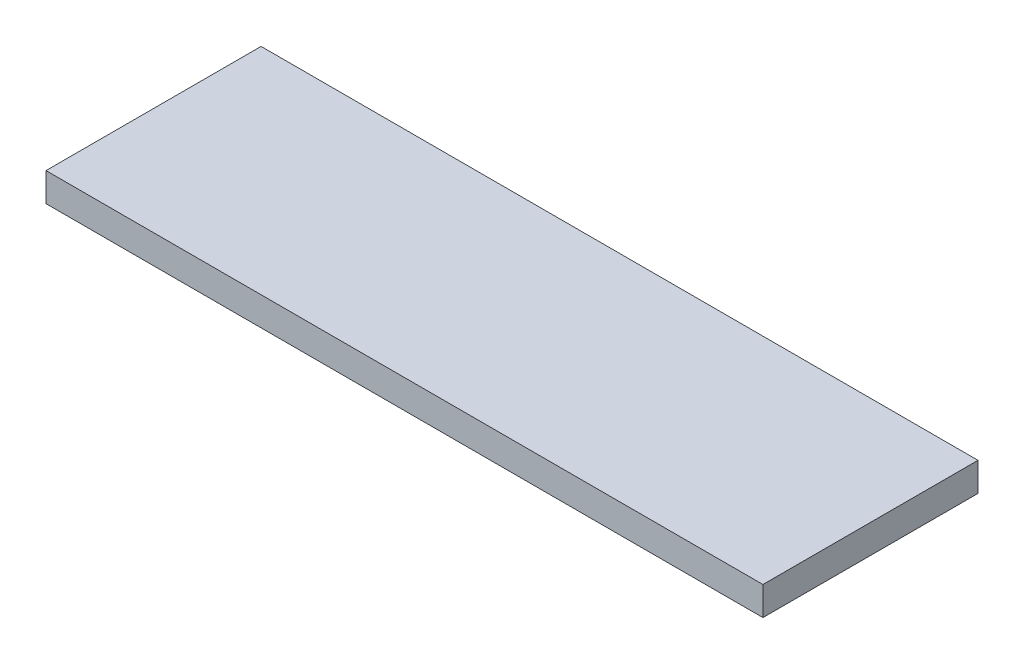
SolidWorks part; units mm, degrees
ref_plane "Front Plane" through (0, 0, 0) normal (0, 0, 1) x (1, 0, 0)
ref_plane "Top Plane" through (0, 0, 0) normal (0, 1, 0) x (1, 0, 0)
ref_plane "Right Plane" through (0, 0, 0) normal (1, 0, 0) x (0, 0, -1)
sketch "Sketch1" plane through (0, 0, 0) normal (0, 1, 0) x (1, 0, 0)
  line L1 (0, 0) -> (50, 0)
  line L2 (0, 0) -> (0, 15)
  line L3 (0, 15) -> (50, 15)
  line L4 (50, 0) -> (50, 15)
  dimension "D1" = 15
  dimension "D2" = 50
extrude "Boss-Extrude1" add sketch "Sketch1" along normal blind 2
